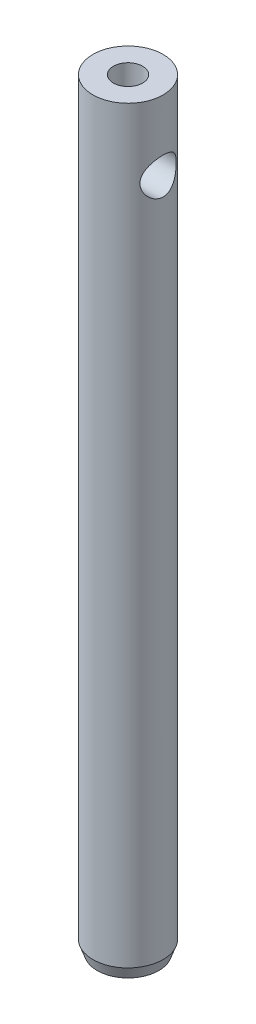
SolidWorks part; units mm, degrees
material "SUS304"
ref_plane "Front" through (0, 0, 0) normal (0, 0, 1) x (1, 0, 0)
ref_plane "Top" through (0, 0, 0) normal (0, 1, 0) x (1, 0, 0)
ref_plane "Right" through (0, 0, 0) normal (1, 0, 0) x (0, 0, -1)
sketch "Sketch1" plane through (0, 0, 0) normal (0, 0, 1) x (1, 0, 0)
  line L0 (0, -5.4289) -> (0, 99.3612) construction
  line L2 (0, 0) -> (3, 0)
  line L3 (0, 0) -> (0, 65)
  line L4 (0, 65) -> (3, 65)
  line L5 (3, 0) -> (3, 65)
  dimension "D1" = 65
  dimension "D2" = 6
revolve "Revolve1" add sketch "Sketch1" angle 360 about L0
sketch "Sketch2" plane through (0, 0, 0) normal (1, 0, 0) x (0, 0, -1)
  circle A0 centre (0, 59) radius 1.55
  dimension "D2" = 3.1
  dimension "D1" = 59
extrude "Cut-Extrude1" cut sketch "Sketch2" against normal through all and the other way through all
hole_wizard "M3x0.5 Tapped Hole1" positions "Sketch4" profile "Sketch3" tap size "M3x0.5" standard "JIS"
sketch "Sketch4" plane through (0, 65, 0) normal (0, 1, 0) x (-1, 0, 0)
  point P0 (0, 0)
sketch "Sketch3" plane through (0, 65, 0) normal (1, 0, 0) x (0, 0, 1)
  line L0 (0, 0) -> (0, 4.45)
  line L1 (0, 4.45) -> (1.25, 4.45)
  line L2 (1.25, 4.45) -> (1.25, 0)
  line L5 (1.25, 0) -> (0, 0)
  line L11 (0, -6.35) -> (0, 107.95) construction
  dimension "Thru Tap Drill Dia." = 2.5
  dimension "Thru Tap Drill Depth" = 4.45
cosmetic thread "Hole Thread1" parameters "D2"=3
chamfer "Chamfer1" distance 1 angle 20 1 edges at (0, 0, -3)
